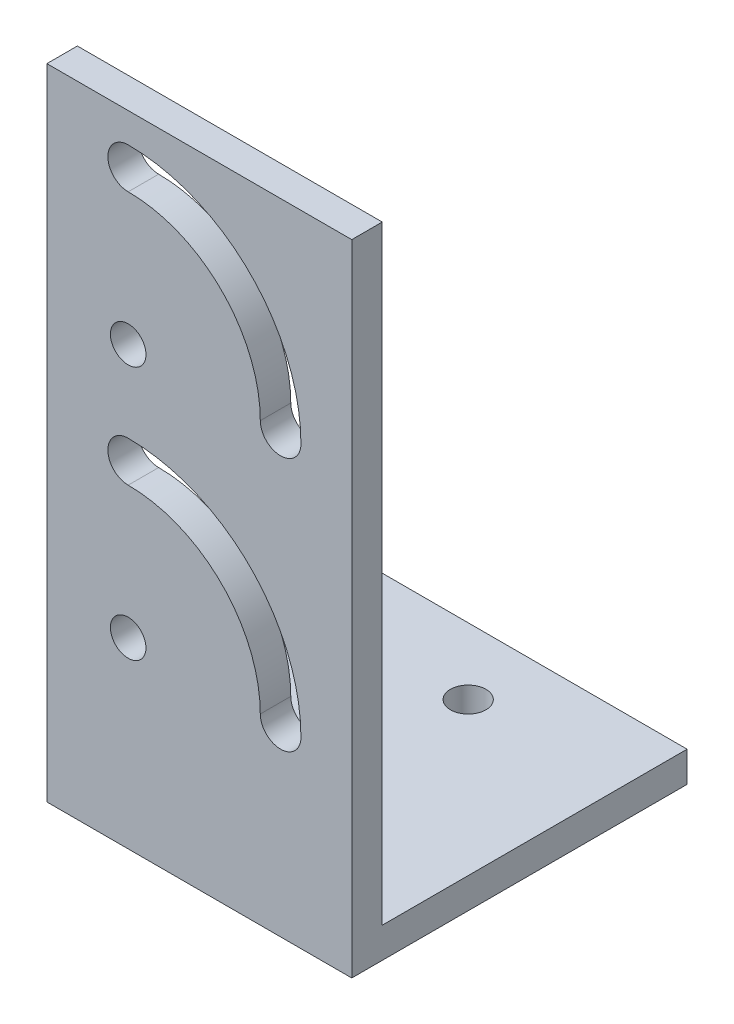
SolidWorks part; units mm, degrees
ref_plane "前视基准面" through (0, 0, 0) normal (0, 0, 1) x (1, 0, 0)
ref_plane "上视基准面" through (0, 0, 0) normal (0, 1, 0) x (1, 0, 0)
ref_plane "右视基准面" through (0, 0, 0) normal (1, 0, 0) x (0, 0, -1)
sketch "草图1" plane through (0, 0, 0) normal (0, 1, 0) x (1, 0, 0)
  line L1 (-15, -15) -> (15, -15)
  line L2 (-15, -15) -> (-15, 15)
  line L3 (-15, 15) -> (15, 15)
  line L4 (15, -15) -> (15, 15)
  line L5 (-15, -15) -> (15, 15) construction
  line L6 (-15, 15) -> (15, -15) construction
  point P1 (0, 0)
  dimension "D1" = 30
  dimension "D2" = 30
extrude "凸台-拉伸1" add sketch "草图1" along normal blind 3
sketch "草图2" plane through (0, 3, 0) normal (0, 1, 0) x (1, 0, 0)
  circle A0 centre (0, -6.5427) radius 1.75
  circle A1 centre (0, 8.4573) radius 1.75
  dimension "D1" = 15
extrude "切除-拉伸1" cut sketch "草图2" against normal blind 3
sketch "草图3" plane through (0, 0, 15) normal (0, 0, 1) x (1, 0, 0)
  line L1 (-15, 0) -> (15, 0)
  line L2 (-15, 0) -> (-15, 62.9242)
  line L3 (-15, 62.9242) -> (15, 62.9242)
  line L4 (15, 0) -> (15, 62.9242)
  point P5 (15, 0)
extrude "凸台-拉伸2" add sketch "草图3" along normal blind 3
sketch "草图4" plane through (0, 0, 18) normal (0, 0, 1) x (1, 0, 0)
  line L0 (-15, 62.9242) -> (-15, 0) construction
  line L1 (15, 0) -> (15, 62.9242) construction
  line L2 (-15, 0) -> (15, 0) construction
  arc A1 (6, 18) -> (-7, 31) centre (-7, 18) ccw
  arc A2 (10, 18) -> (-7, 35) centre (-7, 18) ccw
  arc A3 (-7, 35) -> (-7, 31) centre (-7, 33) ccw
  arc A4 (6, 18) -> (10, 18) centre (8, 18) ccw
  circle A5 centre (-7, 18) radius 1.75
  arc A6 (6, 43) -> (10, 43) centre (8, 43) ccw
  arc A7 (6, 43) -> (-7, 56) centre (-7, 43) ccw
  arc A8 (10, 43) -> (-7, 60) centre (-7, 43) ccw
  arc A9 (-7, 60) -> (-7, 56) centre (-7, 58) ccw
  circle A10 centre (-7, 43) radius 1.75
  dimension "D1" = 3.5
  dimension "D2" = 4
  dimension "D3" = 4
  dimension "D4" = 13
  dimension "D5" = 17
  dimension "D6" = 8
  dimension "D7" = 7
  dimension "D8" = 18
  dimension "D9" = 2
extrude "切除-拉伸2" cut sketch "草图4" against normal blind 3
